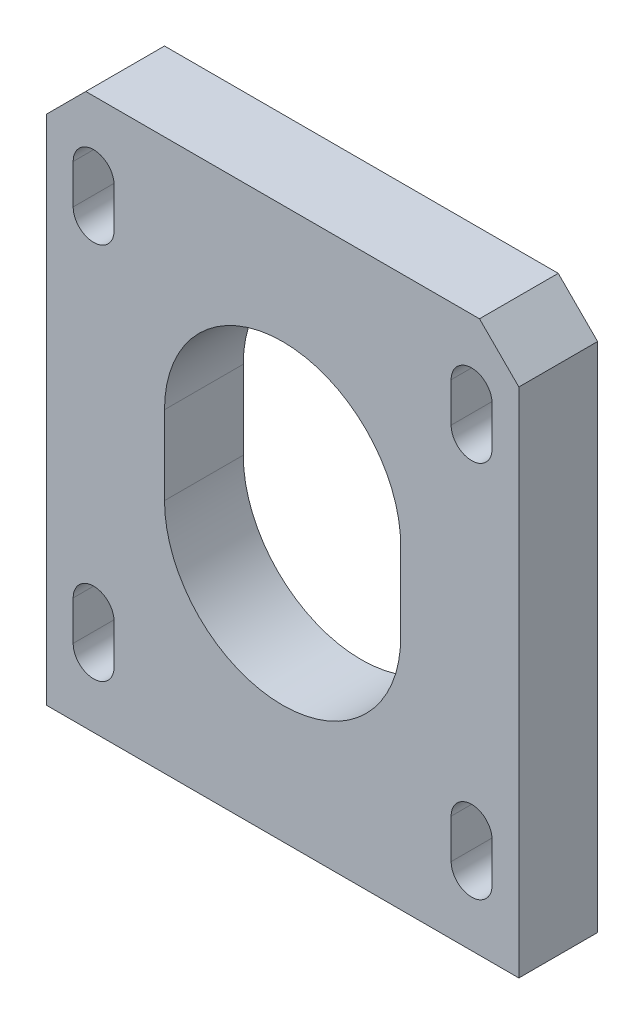
SolidWorks part; units mm, degrees
ref_plane "Plan de face" through (0, 0, 0) normal (0, 0, 1) x (1, 0, 0)
ref_plane "Plan de dessus" through (0, 0, 0) normal (0, 1, 0) x (1, 0, 0)
ref_plane "Plan de droite" through (0, 0, 0) normal (1, 0, 0) x (0, 0, -1)
sketch "Esquisse1" plane through (0, 0, 0) normal (0, 0, 1) x (1, 0, 0)
  line L1 (0, 0) -> (60, 0)
  line L2 (0, 0) -> (0, 70)
  line L3 (0, 70) -> (60, 70)
  line L4 (60, 0) -> (60, 70)
  dimension "D1" = 60
  dimension "D2" = 70
extrude "Boss.-Extru.1" add sketch "Esquisse1" along normal blind 10
sketch "Esquisse2" plane through (0, 0, 10) normal (0, 0, 1) x (1, 0, 0)
  line L0 (30, 0) -> (30, 70) construction
  line L1 (0, 0) -> (60, 0) construction
  line L2 (60, 70) -> (0, 70) construction
  line L3 (0, 35) -> (60, 35) construction
  line L4 (0, 70) -> (0, 0) construction
  line L5 (60, 0) -> (60, 70) construction
  line L6 (6, 61.5) -> (6, 56.5) construction
  line L7 (8.6, 61.5) -> (8.6, 56.5)
  line L8 (3.4, 61.5) -> (3.4, 56.5)
  line L9 (54, 61.5) -> (54, 56.5) construction
  line L10 (51.4, 61.5) -> (51.4, 56.5)
  line L11 (56.6, 61.5) -> (56.6, 56.5)
  line L12 (54, 8.5) -> (54, 13.5) construction
  line L13 (51.4, 8.5) -> (51.4, 13.5)
  line L14 (56.6, 8.5) -> (56.6, 13.5)
  line L15 (6, 8.5) -> (6, 13.5) construction
  line L16 (8.6, 8.5) -> (8.6, 13.5)
  line L17 (3.4, 8.5) -> (3.4, 13.5)
  line L18 (30, 30) -> (30, 40) construction
  line L19 (15, 30) -> (15, 40)
  line L20 (45, 30) -> (45, 40)
  arc A0 (8.6, 61.5) -> (3.4, 61.5) centre (6, 61.5) ccw
  arc A1 (3.4, 56.5) -> (8.6, 56.5) centre (6, 56.5) ccw
  arc A2 (51.4, 61.5) -> (56.6, 61.5) centre (54, 61.5) cw
  arc A3 (56.6, 56.5) -> (51.4, 56.5) centre (54, 56.5) cw
  arc A4 (51.4, 8.5) -> (56.6, 8.5) centre (54, 8.5) ccw
  arc A5 (56.6, 13.5) -> (51.4, 13.5) centre (54, 13.5) ccw
  arc A6 (8.6, 8.5) -> (3.4, 8.5) centre (6, 8.5) cw
  arc A7 (3.4, 13.5) -> (8.6, 13.5) centre (6, 13.5) cw
  arc A8 (15, 30) -> (45, 30) centre (30, 30) ccw
  arc A9 (45, 40) -> (15, 40) centre (30, 40) ccw
  point P14 (6, 59)
  point P21 (54, 59)
  point P28 (54, 11)
  point P35 (6, 11)
  point P42 (30, 35)
  dimension "D4" = 2.6
  dimension "D5" = 15
  dimension "D1" = 48
  dimension "D2" = 48
  dimension "D3" = 5
  dimension "D6" = 10
extrude "Enlèv. mat.-Extru.1" cut sketch "Esquisse2" against normal blind 10
chamfer "Chanfrein1" distance 5 angle 45 2 edges at (60, 70, 5) (0, 70, 5)
